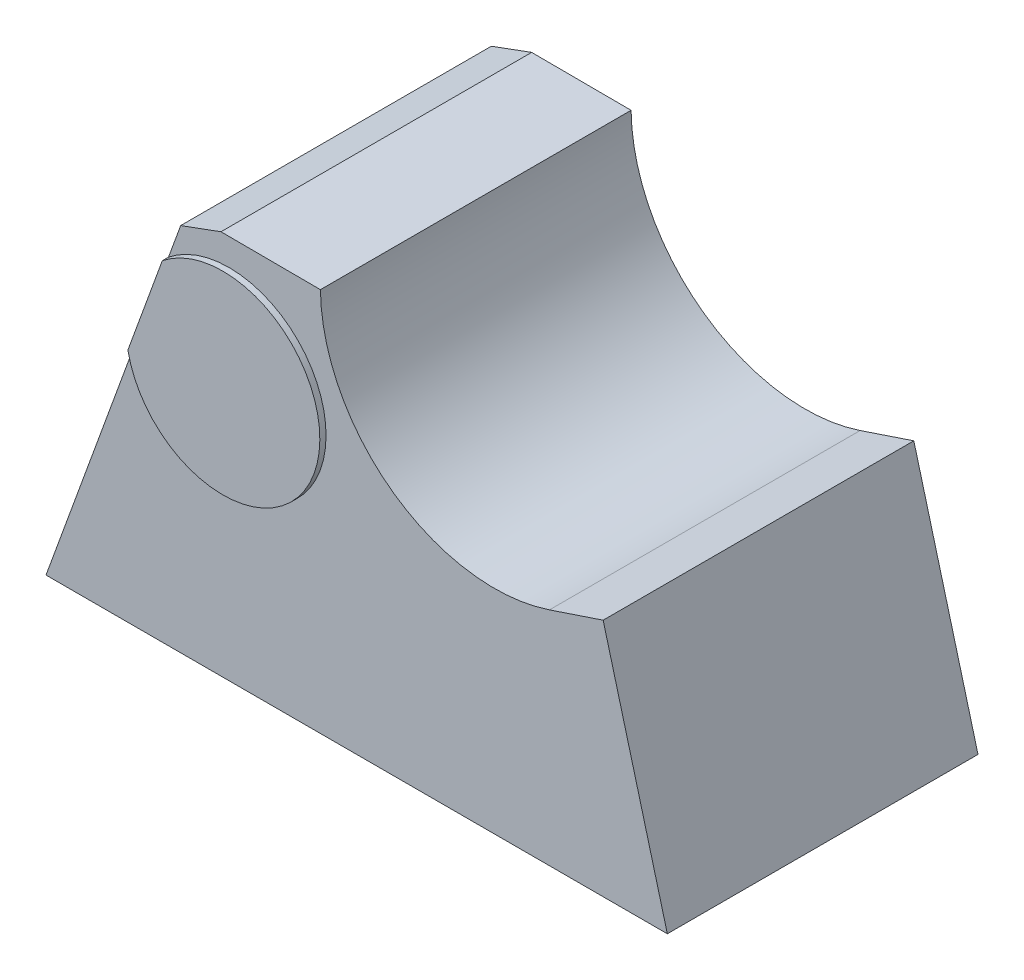
SolidWorks part; units mm, degrees
ref_plane "Front Plane" through (0, 0, 0) normal (0, 0, 1) x (1, 0, 0)
ref_plane "Top Plane" through (0, 0, 0) normal (0, 1, 0) x (1, 0, 0)
ref_plane "Right Plane" through (0, 0, 0) normal (1, 0, 0) x (0, 0, -1)
sketch "Sketch2" plane through (0, 0, 0) normal (0, 0, 1) x (1, 0, 0)
  line L0 (0, 0) -> (0, -258)
  line L1 (0, -258) -> (500, -258)
  line L2 (500, -258) -> (500, -48)
  line L3 (500, -48) -> (405.1491, -79.675)
  line L4 (220.8156, 51.325) -> (140.8163, 51.6794)
  line L5 (140.8163, 51.6794) -> (0, 0)
  arc A0 (405.1491, -79.675) -> (220.8156, 51.325) centre (360.8041, 53.1163) cw
  dimension "D1" = 500
  dimension "D7" = 140
  dimension "D2" = 258
  dimension "D3" = 210
  dimension "D4" = 100
  dimension "D5" = 150
  dimension "D6" = 131
  dimension "D9" = 51.325
extrude "Boss-Extrude1" add sketch "Sketch2" against normal blind 250
sketch "Sketch3" plane through (0, 0, 0) normal (0, 0, 1) x (1, 0, 0)
  circle A0 centre (147.3656, -47.9845) radius 83
  circle A1 centre (147.3656, -47.9845) radius 78
  dimension "D1" = 166
extrude "Boss-Extrude2" add sketch "Sketch3" along normal blind 5 contours A1
sketch "Sketch4" plane through (0, 0, 0) normal (0, 0, 1) x (1, 0, 0)
  line L1 (23.5627, -22.5157) -> (43.5627, -22.5157)
  line L2 (23.5627, -22.5157) -> (23.5627, -72.5157)
  line L3 (23.5627, -72.5157) -> (43.5627, -72.5157)
  line L4 (43.5627, -22.5157) -> (43.5627, -72.5157)
  dimension "D1" = 20
  dimension "D2" = 50
extrude "Boss-Extrude3" add sketch "Sketch4" along normal blind 8
sketch "Sketch5" plane through (0, 0, -250) normal (0, 0, -1) x (-1, 0, 0)
  circle A2 centre (-147.3656, -47.9845) radius 61
  circle A3 centre (-147.3656, -47.9845) radius 56
extrude "Boss-Extrude4" add sketch "Sketch5" along normal blind 5 contours A3
sketch "Sketch6" plane through (0, 0, -250) normal (0, 0, -1) x (-1, 0, 0)
  line L1 (-77.2041, -242.2657) -> (-217.5271, -242.2657)
  line L2 (-77.2041, -242.2657) -> (-77.2041, -122.2657)
  line L3 (-77.2041, -122.2657) -> (-217.5271, -122.2657)
  line L4 (-217.5271, -242.2657) -> (-217.5271, -122.2657)
  line L5 (-77.2041, -242.2657) -> (-217.5271, -122.2657) construction
  line L6 (-77.2041, -122.2657) -> (-217.5271, -242.2657) construction
  circle A0 centre (-147.3656, -47.9845) radius 56 construction
  circle A1 centre (-147.3656, -47.9845) radius 56
  point P0 (-147.3656, -182.2657)
  dimension "D1" = 120
extrude "Boss-Extrude5" add sketch "Sketch6" along normal blind 8 contours L4 L1 L2 L3
sketch "Sketch8" plane through (0, 0, -250) normal (0, 0, -1) x (-1, 0, 0)
  line L0 (-500, -258) -> (-500, -78.4025)
  line L1 (-500, -258) -> (-500, -48) construction
  line L2 (-500, -258) -> (-457.6373, -99.9004)
  line L3 (-457.6373, -99.9004) -> (-446.3349, -57.7191)
  line L4 (-446.3349, -57.7191) -> (-500, -48)
  arc A0 (-405.1491, -79.675) -> (-220.8156, 51.325) centre (-360.8041, 53.1163) ccw construction
  arc M12 (-220.8156, 51.325) -> (-405.1491, -79.675) centre (-360.8041, 53.1163) cw
  line M13 (-405.1491, -79.675) -> (-500, -48)
  line M14 (-500, -48) -> (-500, -258)
  dimension "D1" = 15
extrude "Cut-Extrude1" cut sketch "Sketch8" against normal through all and the other way through all contours L2 L3 M12 M13 M14
sketch "Sketch9" plane through (0, 0, -250) normal (0, 0, -1) x (-1, 0, 0)
  line L0 (0, -258) -> (0, -19.2487)
  line L1 (0, 0) -> (0, -258) construction
  line L2 (0, -258) -> (-65.4514, -78.1738)
  line L3 (-65.4514, -78.1738) -> (-108.3816, 39.7759)
  line L4 (-140.8163, 51.6794) -> (0, 0) construction
  line L5 (-108.3816, 39.7759) -> (0, 0)
  line M7 (0, -258) -> (0, 0)
  line M8 (0, 0) -> (-140.8163, 51.6794)
  dimension "D1" = 20
extrude "Cut-Extrude2" cut sketch "Sketch9" against normal through all and the other way through all contours L3 L2 M7 M8
